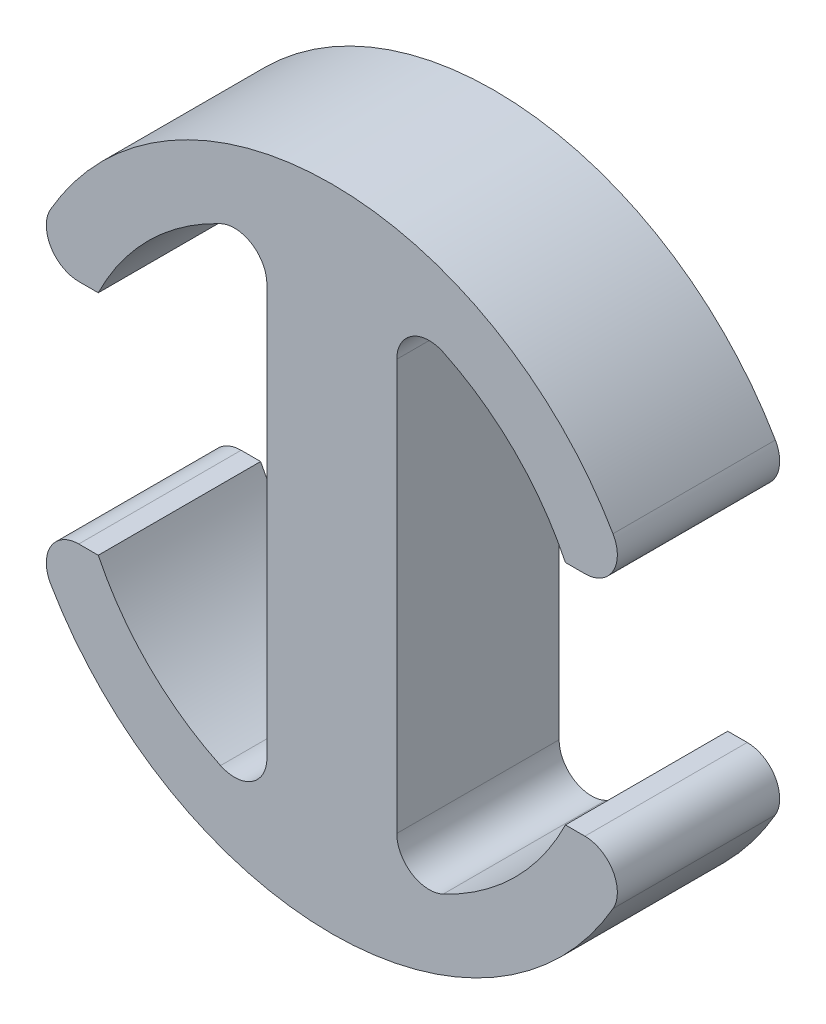
SolidWorks part; units mm, degrees
ref_plane "Front Plane" through (0, 0, 0) normal (0, 0, 1) x (1, 0, 0)
ref_plane "Top Plane" through (0, 0, 0) normal (0, 1, 0) x (1, 0, 0)
ref_plane "Right Plane" through (0, 0, 0) normal (1, 0, 0) x (0, 0, -1)
sketch "Sketch1" plane through (0, 0, 0) normal (0, 0, 1) x (1, 0, 0)
  line L0 (0, 0) -> (0, 6.3457) construction
  line L2 (-2, -6.3246) -> (-2, 6.3246)
  line L4 (2, -6.3246) -> (2, 6.3246)
  line L5 (0, 0) -> (5.0512, 0) construction
  line L6 (-7.7942, 3.5) -> (-7.1937, 3.5)
  line L7 (-7.1937, -3.5) -> (-7.7942, -3.5)
  line L8 (7.7942, 3.5) -> (7.1937, 3.5)
  line L10 (7.1937, -3.5) -> (7.7942, -3.5)
  arc A0 (-8.6603, -5) -> (8.6603, -5) centre (0, 0) ccw
  arc A1 (-7.1937, -3.5) -> (-3.4286, -7.2281) centre (0, 0) ccw
  arc A2 (7.1937, 3.5) -> (3.4286, 7.2281) centre (0, 0) ccw
  arc A3 (8.6603, 5) -> (-8.6603, 5) centre (0, 0) ccw
  arc A4 (-3.4286, 7.2281) -> (-7.1937, 3.5) centre (0, 0) ccw
  arc A5 (3.4286, -7.2281) -> (7.1937, -3.5) centre (0, 0) ccw
  arc A6 (-7.7942, 3.5) -> (-8.6603, 5) centre (-7.7942, 4.5) cw
  arc A7 (8.6603, 5) -> (7.7942, 3.5) centre (7.7942, 4.5) cw
  arc A8 (8.6603, -5) -> (7.7942, -3.5) centre (7.7942, -4.5) ccw
  arc A9 (-7.7942, -3.5) -> (-8.6603, -5) centre (-7.7942, -4.5) ccw
  arc A10 (-2, -6.3246) -> (-3.4286, -7.2281) centre (-3, -6.3246) cw
  arc A11 (3.4286, -7.2281) -> (2, -6.3246) centre (3, -6.3246) cw
  arc A12 (3.4286, 7.2281) -> (2, 6.3246) centre (3, 6.3246) ccw
  arc A13 (-2, 6.3246) -> (-3.4286, 7.2281) centre (-3, 6.3246) ccw
  point P20 (9.3675, 3.5)
  point P33 (-2, 7.746)
  dimension "D1" = 20
  dimension "D2" = 16
  dimension "D5" = 1
  dimension "D3" = 4
  dimension "D4" = 7
extrude "Boss-Extrude1" add sketch "Sketch1" along normal blind 5 contours A4 L6 A6 A3 A7 L8 A2 A12 L4 A11 A5 L10 A8 A0 A9 L7 A1 A10 L2 A13
